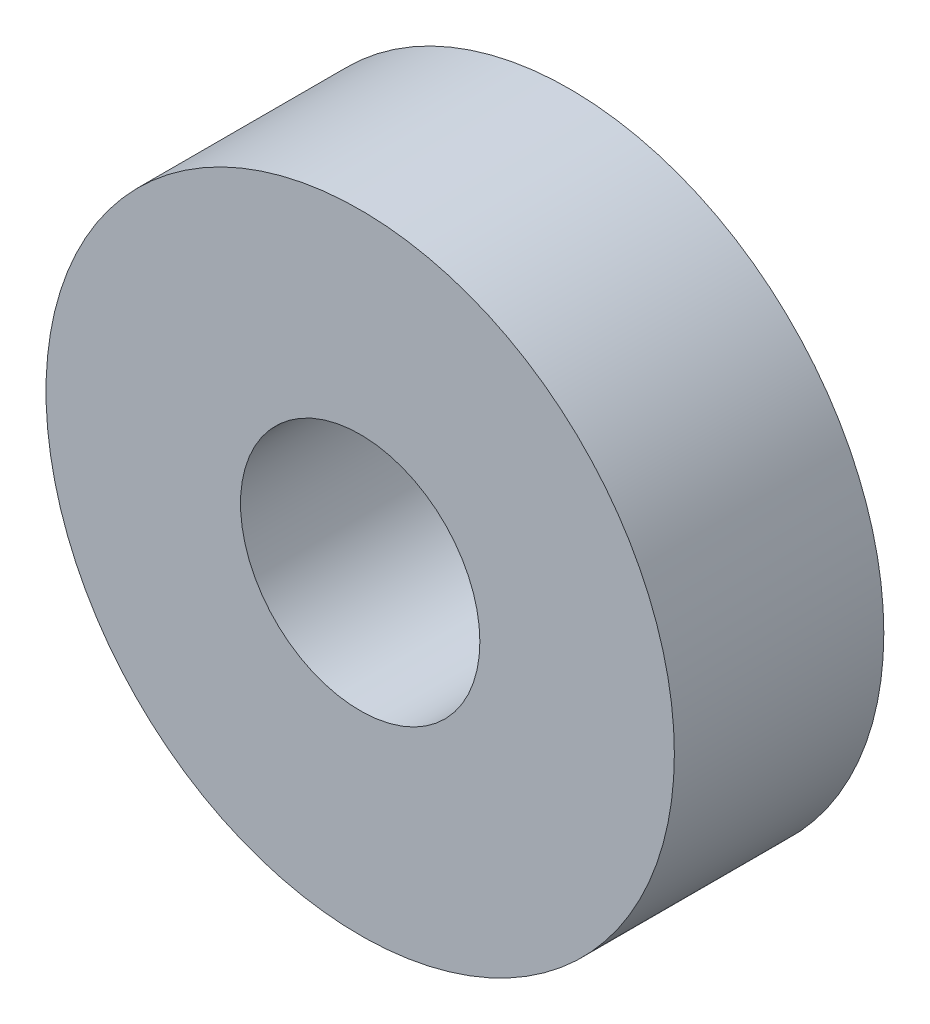
SolidWorks part; units mm, degrees
ref_plane "Plan de face" through (0, 0, 0) normal (0, 0, 1) x (1, 0, 0)
ref_plane "Plan de dessus" through (0, 0, 0) normal (0, 1, 0) x (1, 0, 0)
ref_plane "Plan de droite" through (0, 0, 0) normal (1, 0, 0) x (0, 0, -1)
sketch "Esquisse1" plane through (0, 0, 0) normal (0, 0, 1) x (1, 0, 0)
  circle A2 centre (0, 0) radius 4
  circle A3 centre (0, 0) radius 10.5
  dimension "D1" = 21
  dimension "D2" = 8
extrude "Boss.-Extru.1" add sketch "Esquisse1" along normal blind 7
